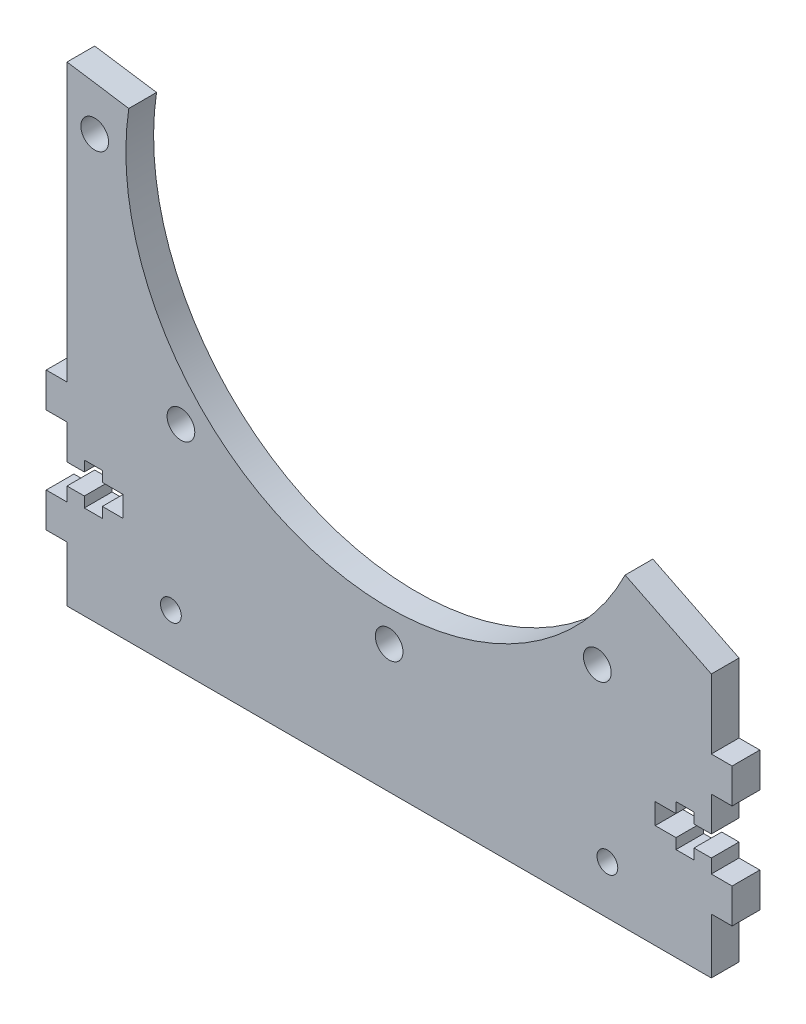
SolidWorks part; units mm, degrees
ref_plane "前视基准面" through (0, 0, 0) normal (0, 0, 1) x (1, 0, 0)
ref_plane "上视基准面" through (0, 0, 0) normal (0, 1, 0) x (1, 0, 0)
ref_plane "右视基准面" through (0, 0, 0) normal (1, 0, 0) x (0, 0, -1)
sketch "草图3" plane through (0, 0, 0) normal (0, 0, 1) x (1, 0, 0)
  line L1 (-46.5, -7.9902) -> (46.5, -7.9902)
  line L2 (-46.5, -1.9902) -> (-46.5, 0.0098) construction
  line L4 (46.5, -1.9902) -> (46.5, 0.0098) construction
  line L10 (0, -1.9902) -> (0, 3.216) construction
  line L27 (-46.5, 0.0098) -> (-46.5, -7.9902)
  line L30 (46.5, 0.0098) -> (46.5, -7.9902)
  line L37 (46.5, 30.0098) -> (34.0612, 36.1623)
  line L38 (-46.5, 60.0098) -> (-37.5766, 58.6665)
  line L39 (-46.5, 0.0098) -> (-49.5, 0.0098)
  line L40 (-49.5, 0.0098) -> (-49.5, 5.0098)
  line L41 (-49.5, 5.0098) -> (-46.5, 5.0098)
  line L42 (-44, 7.0098) -> (-44, 5.5098)
  line L43 (-44, 10.0098) -> (-44, 11.5098)
  line L44 (-46.5, 10.0098) -> (-44, 10.0098)
  line L45 (-44, 5.5098) -> (-41.4, 5.5098)
  line L46 (-41.4, 5.5098) -> (-41.4, 7.0098)
  line L47 (-41.4, 7.0098) -> (-38.4, 7.0098)
  line L48 (-38.4, 10.0098) -> (-38.4, 7.0098)
  line L49 (-41.4, 10.0098) -> (-38.4, 10.0098)
  line L50 (-41.4, 11.5098) -> (-41.4, 10.0098)
  line L51 (-44, 11.5098) -> (-41.4, 11.5098)
  line L52 (-44, 7.0098) -> (-46.5, 7.0098)
  line L53 (-46.5, 5.0098) -> (-46.5, 7.0098)
  line L54 (-46.5, 10.0098) -> (-46.5, 15.0098)
  line L55 (-46.5, 15.0098) -> (-49.5, 15.0098)
  line L56 (-49.5, 15.0098) -> (-49.5, 20.0098)
  line L57 (-49.5, 20.0098) -> (-46.5, 20.0098)
  line L58 (-46.5, 20.0098) -> (-46.5, 60.0098)
  line L59 (49.5, 20.0098) -> (46.5, 20.0098)
  line L60 (49.5, 15.0098) -> (49.5, 20.0098)
  line L61 (46.5, 15.0098) -> (49.5, 15.0098)
  line L62 (46.5, 10.0098) -> (46.5, 15.0098)
  line L63 (46.5, 5.0098) -> (46.5, 7.0098)
  line L64 (44, 7.0098) -> (46.5, 7.0098)
  line L65 (44, 11.5098) -> (41.4, 11.5098)
  line L66 (41.4, 11.5098) -> (41.4, 10.0098)
  line L67 (41.4, 10.0098) -> (38.4, 10.0098)
  line L68 (38.4, 10.0098) -> (38.4, 7.0098)
  line L69 (41.4, 7.0098) -> (38.4, 7.0098)
  line L70 (41.4, 5.5098) -> (41.4, 7.0098)
  line L71 (44, 5.5098) -> (41.4, 5.5098)
  line L72 (46.5, 10.0098) -> (44, 10.0098)
  line L73 (44, 10.0098) -> (44, 11.5098)
  line L74 (44, 7.0098) -> (44, 5.5098)
  line L75 (49.5, 5.0098) -> (46.5, 5.0098)
  line L76 (46.5, 0.0098) -> (49.5, 0.0098)
  line L77 (49.5, 0.0098) -> (49.5, 5.0098)
  line L78 (46.5, 20.0098) -> (46.5, 30.0098)
  circle A0 centre (-31.5, -0.9902) radius 1.5
  circle A1 centre (31.5, -0.9902) radius 1.5
  circle A4 centre (0, 10.5098) radius 2
  circle A5 centre (-30.052, 22.9577) radius 2
  circle A6 centre (-42.5, 53.0098) radius 2
  circle A11 centre (30.052, 22.9577) radius 2
  arc A12 (-37.5766, 58.6665) -> (34.0612, 36.1623) centre (0, 53.0098) ccw
  circle A13 centre (42.5, 53.0098) radius 2 [skipped]
  circle A14 centre (30.052, 83.0618) radius 2 [skipped]
  circle A15 centre (-30.052, 83.0618) radius 2 [skipped]
  circle A16 centre (0, 95.5098) radius 2 [skipped]
  dimension "D1" = 8
extrude "凸台-拉伸1" add sketch "草图3" along normal blind 4
sketch "草图4" plane through (46.5, 0, 0) normal (1, 0, 0) x (0, 0, -1)
  line L0 (-4, 10.0098) -> (0, 7.0098)
  circle A0 centre (-2, 8.5098) radius 1.5
sketch "草图5" plane through (-46.5, 0, 0) normal (-1, 0, 0) x (0, 0, 1)
  line L0 (0, 10.0098) -> (4, 7.0098)
  circle A0 centre (2, 8.5098) radius 1.5
